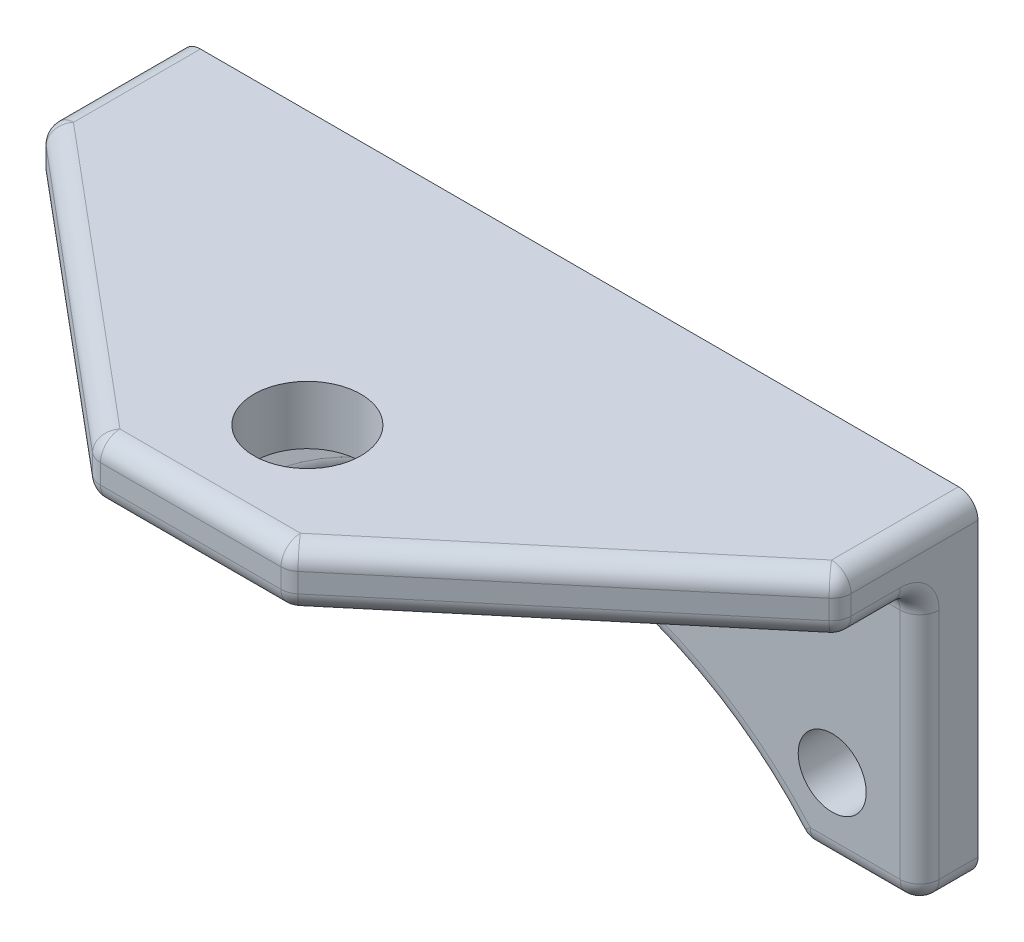
SolidWorks part; units mm, degrees
material "ABS"
ref_plane "Front Plane" through (0, 0, 0) normal (0, 0, 1) x (1, 0, 0)
ref_plane "Top Plane" through (0, 0, 0) normal (0, 1, 0) x (1, 0, 0)
ref_plane "Right Plane" through (0, 0, 0) normal (1, 0, 0) x (0, 0, -1)
sketch "Sketch1" plane through (0, 0, 0) normal (0, 0, 1) x (1, 0, 0)
  line L0 (-20.5, 7) -> (-20.5, -7)
  line L1 (-20.5, 7) -> (20.5, 7)
  line L2 (-20.5, -7) -> (-14.407, -7)
  line L3 (20.5, 7) -> (20.5, -7)
  line L4 (-20.5, 7) -> (20.5, -7) construction
  line L5 (-20.5, -7) -> (20.5, 7) construction
  line L6 (14.407, -7) -> (20.5, -7)
  line L7 (0, 7) -> (0, -19) construction
  arc A0 (14.407, -7) -> (-14.407, -7) centre (0, -19) ccw
  circle A1 centre (-16, -3) radius 1.75
  circle A2 centre (16, -3) radius 1.75
  point P1 (0, 0)
  dimension "D2" = 18.75
  dimension "D5" = 16
  dimension "D7" = 3.5
  dimension "D1" = 41
  dimension "D3" = 26
  dimension "D4" = 14
  dimension "D6" = 16
extrude "Boss-Extrude1" add sketch "Sketch1" along normal blind 3
sketch "Sketch2" plane through (0, 7, 0) normal (0, 1, 0) x (1, 0, 0)
  line L0 (-20.5, 0) -> (20.5, 0)
  line L1 (-20.5, 0) -> (-20.5, -7)
  line L2 (20.5, 0) -> (20.5, -7)
  line L3 (-5.0072, -20) -> (5.0072, -20)
  line L4 (-20.5, -7) -> (-5.0072, -20)
  line L5 (20.5, -7) -> (5.0072, -20)
  line L6 (0, 0) -> (0, -17) construction
  circle A0 centre (0, -14) radius 2.75
  point P4 (20.5, -20)
  point P5 (-20.5, -20)
  dimension "D6" = 5.5
  dimension "D7" = 6
  dimension "D1" = 20
  dimension "D2" = 13
  dimension "D3" = 50
  dimension "D4" = 13
  dimension "D5" = 50
extrude "Boss-Extrude2" add sketch "Sketch2" along normal blind 3
fillet "Fillet1" radius 1 24 edges at (-12.7536, 7, 13.5) (-12.7536, 10, 13.5) (0, 7, 20) (0, 10, 20) (12.7536, 7, 13.5) (12.7536, 10, 13.5) (-17.4535, -7, 3) (0, -0.25, 3) (17.4535, -7, 3) (20.5, 10, 3.5) (-20.5, 10, 3.5) (20.5, -7, 1.5) (-14.407, -7, 1.5) (-20.5, -7, 1.5) (14.407, -7, 1.5) (20.5, 8.5, 7) (5.0072, 8.5, 20) (-5.0072, 8.5, 20) (-20.5, 8.5, 7)
